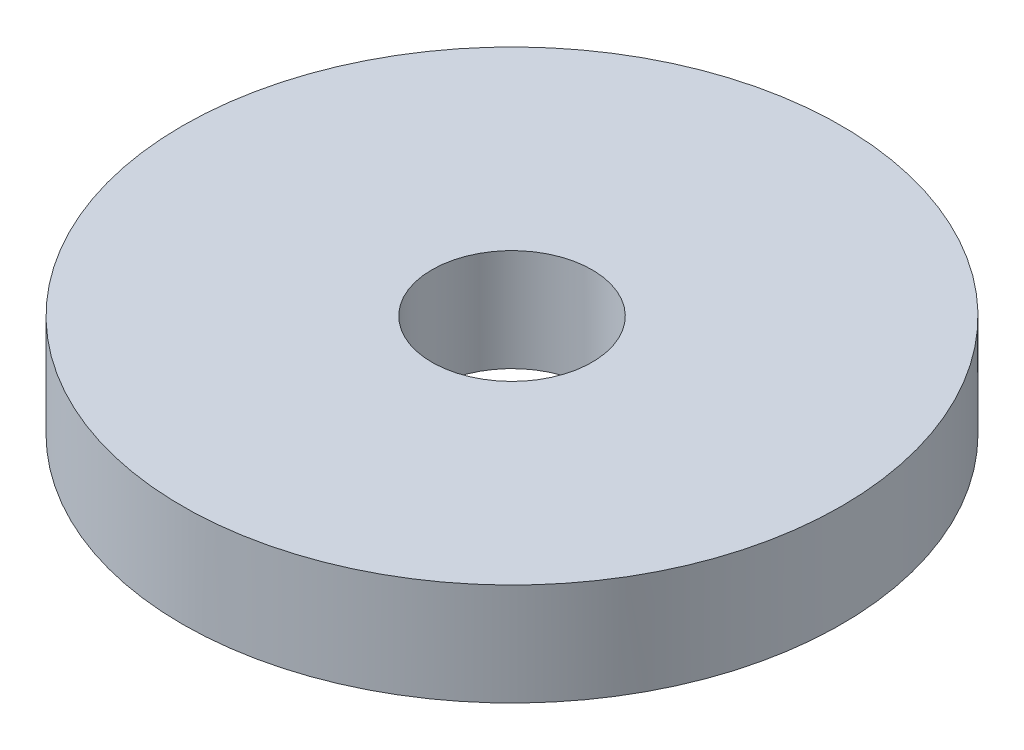
SolidWorks part; units mm, degrees
ref_plane "Front Plane" through (0, 0, 0) normal (0, 0, 1) x (1, 0, 0)
ref_plane "Top Plane" through (0, 0, 0) normal (0, 1, 0) x (1, 0, 0)
ref_plane "Right Plane" through (0, 0, 0) normal (1, 0, 0) x (0, 0, -1)
sketch "Sketch1" plane through (0, 0, 0) normal (0, 1, 0) x (1, 0, 0)
  circle A0 centre (0, 0) radius 2.45
  circle A1 centre (0, 0) radius 10.075
  dimension "D1" = 4.9
  dimension "D2" = 20.15
extrude "Boss-Extrude1" add sketch "Sketch1" along normal up to surface (3.125 mm away)
